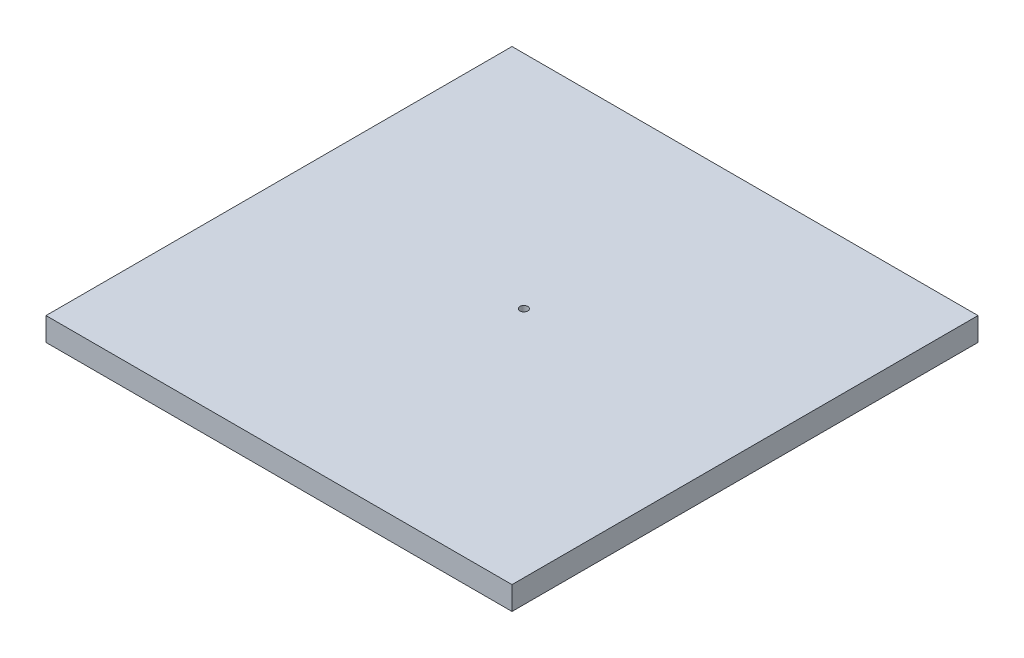
SolidWorks part; units mm, degrees
ref_plane "Plan de face" through (0, 0, 0) normal (0, 0, 1) x (1, 0, 0)
ref_plane "Plan de dessus" through (0, 0, 0) normal (0, 1, 0) x (1, 0, 0)
ref_plane "Plan de droite" through (0, 0, 0) normal (1, 0, 0) x (0, 0, -1)
sketch "Esquisse1" plane through (0, 0, 0) normal (0, 0, 1) x (1, 0, 0)
  line L1 (-200, 20) -> (200, 20)
  line L2 (-200, 20) -> (-200, 0)
  line L3 (-200, 0) -> (200, 0)
  line L4 (200, 20) -> (200, 0)
  dimension "D1" = 20
  dimension "D2" = 400
  dimension "D3" = 200
extrude "Boss.-Extru.1" add sketch "Esquisse1" along normal blind 400 contours L1 L4 L3 L2
sketch "Esquisse2" plane through (0, 0, 0) normal (0, -1, 0) x (1, 0, 0)
  circle A0 centre (0, 189.8197) radius 4
  dimension "D1" = 8
hole_wizard "Trou taraudé M81" positions "Esquisse4" profile "Esquisse3" tap size "M8" standard "ISO" end condition through all
sketch "Esquisse4" plane through (0, 0, 0) normal (0, -1, 0) x (-1, 0, 0)
  point P0 (0, -189.8197)
sketch "Esquisse3" plane through (0, 0, 189.8197) normal (1, 0, 0) x (0, 0, -1)
  line L0 (0, 0) -> (0, 20)
  line L1 (0, 20) -> (3.4, 20)
  line L2 (3.4, 20) -> (3.4, 0)
  line L5 (3.4, 0) -> (0, 0)
  line L11 (0, -6.35) -> (0, 107.95) construction
  dimension "Diamètre du trou pour taraudage jusqu'au prochain" = 6.8
  dimension "Profondeur du trou pour taraudage jusqu'au prochain" = 20
cosmetic thread "Filetage de perçage1" parameters "D2"=8
